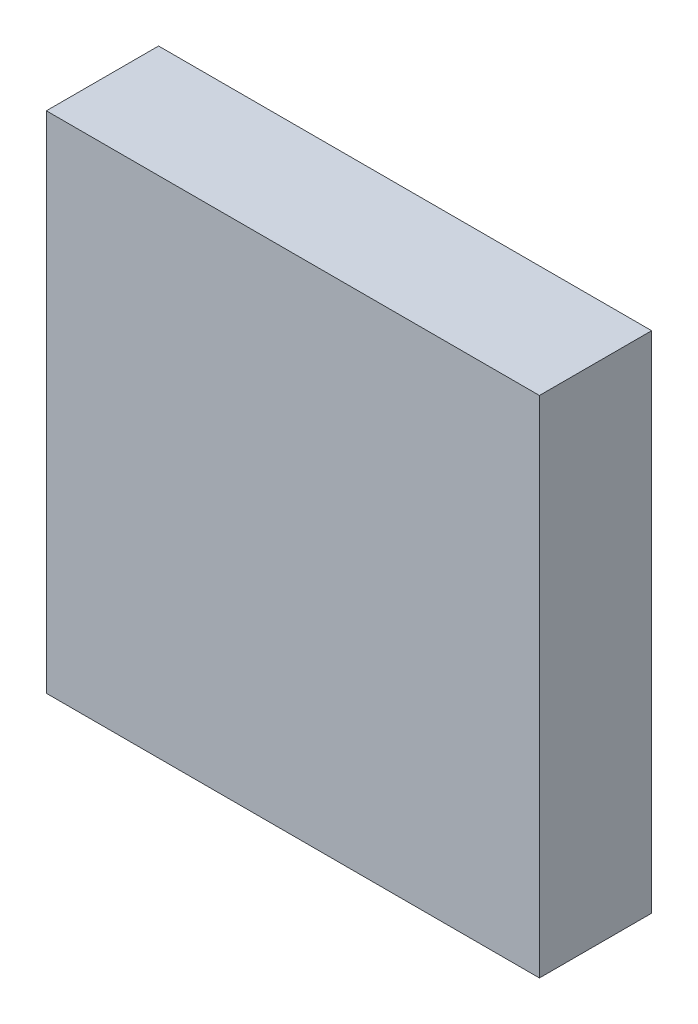
SolidWorks part; units mm, degrees
ref_plane "Front Plane" through (0, 0, 0) normal (0, 0, 1) x (1, 0, 0)
ref_plane "Top Plane" through (0, 0, 0) normal (0, 1, 0) x (1, 0, 0)
ref_plane "Right Plane" through (0, 0, 0) normal (1, 0, 0) x (0, 0, -1)
sketch "Sketch1" plane through (0, 0, 0) normal (0, 0, 1) x (1, 0, 0)
  line L1 (-98, 150) -> (99.7509, 150)
  line L2 (-98, 150) -> (-98, -52.3241)
  line L3 (-98, -52.3241) -> (99.7509, -52.3241)
  line L4 (99.7509, 150) -> (99.7509, -52.3241)
extrude "Boss-Extrude2" add sketch "Sketch1" along normal blind 45
